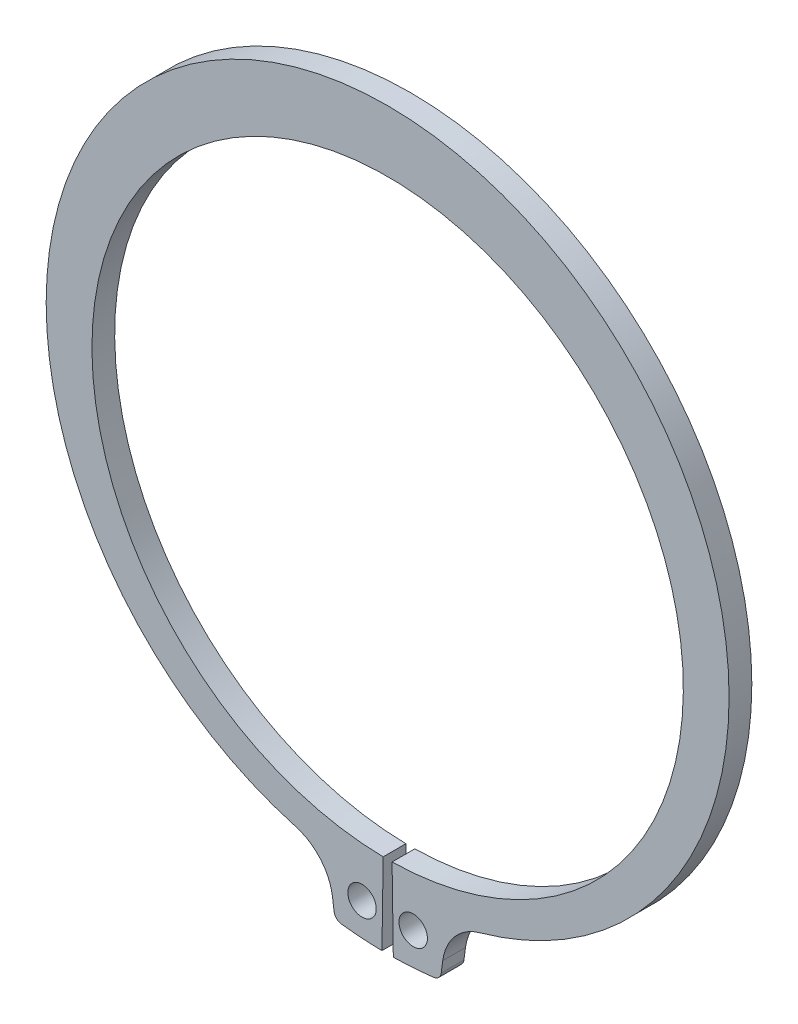
SolidWorks part; units mm, degrees
material "Stahl"
ref_plane "Plane1" through (0, 0, 0) normal (0, 0, 1) x (1, 0, 0)
ref_plane "Plane2" through (0, 0, 0) normal (0, 1, 0) x (1, 0, 0)
ref_plane "Plane3" through (0, 0, 0) normal (1, 0, 0) x (0, 0, -1)
sketch "Clipboard" plane through (0, 0, 0) normal (0, 0, 1) x (1, 0, 0)
  line L0 (0, 0) -> (5.4, 0)
  line L1 (0, 0) -> (0, 2.7)
  line L2 (0, 0) -> (0, -7.2)
  circle A0 centre (0, 0) radius 1.25
  circle A1 centre (0, 0) radius 27.5
  dimension "HoleDia" = 2.5
  dimension "ShaftDia" = 55
  dimension "LargeSection" = 5.4
  dimension "SmallSection" = 2.7
  dimension "LugSection" = 7.2
sketch "BodySke" plane through (0, 0, 0) normal (0, 0, 1) x (1, 0, 0)
  line L0 (-1.5431, 0) -> (1.5431, 0) construction
  line L1 (0, 0) -> (0, 31.4) construction
  line L2 (0.3916, -25.9971) -> (0.5, -33.1962)
  line L3 (-0.3916, -25.9971) -> (-0.5, -33.1962)
  line L4 (0, 0) -> (9.3071, -31.8687) construction
  line L5 (0, 0) -> (-9.3071, -31.8687) construction
  line L7 (4.846, -31.2814) -> (4.7113, -32.3044)
  line L8 (-4.846, -31.2814) -> (-4.7113, -32.3044)
  circle A0 centre (0, 0) radius 26 construction
  arc A1 (0.3916, -25.9971) -> (-0.3916, -25.9971) centre (0, 0) ccw
  arc A2 (8.0456, -27.5492) -> (-8.0456, -27.5492) centre (0, 1.3764) ccw construction
  arc A3 (0.5, -33.1962) -> (4.0594, -32.9509) centre (0, 0) ccw
  arc A4 (8.0941, -27.5357) -> (4.846, -31.2814) centre (9.3071, -31.8687) ccw
  arc A5 (-4.846, -31.2814) -> (-8.0941, -27.5357) centre (-9.3071, -31.8687) ccw
  arc A6 (-4.0594, -32.9509) -> (-0.5, -33.1962) centre (0, 0) ccw
  arc A7 (8.0941, -27.5357) -> (-8.0941, -27.5357) centre (0, 1.3764) ccw
  arc A8 (-5.0237, -29.9313) -> (5.0237, -29.9313) centre (0, 0) ccw construction
  circle A9 centre (2.25, -30.2665) radius 1.25
  circle A10 centre (-2.25, -30.2665) radius 1.25
  arc A11 (4.7113, -32.3044) -> (4.0594, -32.9509) centre (3.9677, -32.2065) cw
  arc A12 (-4.7113, -32.3044) -> (-4.0594, -32.9509) centre (-3.9677, -32.2065) ccw
  point P28 (4.6362, -32.8747)
  point P31 (-4.6362, -32.8747)
  dimension "GrooveDia" = 52
  dimension "D3" = 0.75
  dimension "LugRad" = 33.2
  dimension "HoleOffsetRad" = 30.35
  dimension "HoleDia" = 2.5
  dimension "D2" = 15
  dimension "LargeRad" = 31.4
  dimension "SmallRad" = 28.7
  dimension "Gap" = 1
  dimension "SmallAngle" = 32.56
  dimension "HoleSpacing" = 4.5
extrude "Body" add sketch "BodySke" against normal blind 2
sketch "NotSke" plane through (0, 0, 0) normal (0, 0, 1) x (1, 0, 0)
  line L0 (2.25, -29.0165) -> (2.25, -31.5165)
  line L1 (2.25, -31.5165) -> (-2.25, -31.5165)
  line L2 (-2.25, -31.5165) -> (-2.25, -29.0165)
  line L3 (-2.25, -29.0165) -> (2.25, -29.0165)
  circle A0 centre (2.25, -30.2665) radius 1.25 construction
  circle A1 centre (-2.25, -30.2665) radius 1.25 construction
extrude "Notch" [suppressed] cut sketch "NotSke" against normal through all
sketch "UnlSke" plane through (0, 0, 0) normal (0, 0, 1) x (1, 0, 0)
  line L0 (-3.8228, -32.9792) -> (-2.9938, -25.8271)
  line L1 (3.8228, -32.9792) -> (2.9938, -25.8271)
  arc A0 (2.9938, -25.8271) -> (-2.9938, -25.8271) centre (0, 0) ccw
  arc A1 (3.8228, -32.9792) -> (-3.8228, -32.9792) centre (0, 0) ccw
  arc A2 (0.5, -33.1962) -> (4.0594, -32.9509) centre (0, 0) ccw construction
  arc A3 (0.3916, -25.9971) -> (-0.3916, -25.9971) centre (0, 0) ccw construction
  circle A4 centre (-2.25, -30.2665) radius 1.25 construction
  circle A5 centre (2.25, -30.2665) radius 1.25 construction
extrude "Unlug" [suppressed] add sketch "UnlSke" against normal through all
equation "' \"ShaftDia@Clipboard\" = 3"
equation "' \"Thickness@Body\" = 0.4"
equation "' \"GrooveDia@BodySke\" = 2.8"
equation "' \"LugSection@Clipboard\" = 1.9"
equation "' \"LargeSection@Clipboard\" = 0.8"
equation "' \"HoleDia@Clipboard\" = 1.0"
equation "' \"ShaftDia@Clipboard\" = 10"
equation "' \"Thickness@Body\" = 1.0"
equation "' \"GrooveDia@BodySke\" = 9.6"
equation "' \"LugSection@Clipboard\" = 3.3"
equation "' \"LargeSection@Clipboard\" = 1.8"
equation "' \"HoleDia@Clipboard\" = 1.5"
equation "\"SmallSection@Clipboard\" = \"LargeSection@Clipboard\" * 0.5"
equation "\"Gap@BodySke\" =  \"Thickness@Body\" / 2"
equation "\"LargeRad@BodySke\" =  \"GrooveDia@BodySke\" / 2 +  \"LargeSection@Clipboard\""
equation "\"SmallRad@BodySke\" =  \"GrooveDia@BodySke\" / 2 +  \"SmallSection@Clipboard\""
equation "\"LugRad@BodySke\" = \"GrooveDia@BodySke\" / 2 + \"LugSection@Clipboard\""
equation "\"HoleOffsetRad@BodySke\" = (  \"ShaftDia@Clipboard\" / 2 + \"LugRad@BodySke\" ) / 2"
equation "\"HoleSpacing@BodySke\" = \"Gap@BodySke\"  * 2 +  \"HoleDia@Clipboard\""
equation "\"HoleDia@BodySke\" =  \"HoleDia@Clipboard\""
equation "\"SmallAngle@BodySke\" = atn(\"HoleSpacing@BodySke\" / 2 / sqr(\"HoleOffsetRad@BodySke\"  * \"HoleOffsetRad@BodySke\" - (\"HoleSpacing@BodySke\" / 2) * (\"HoleSpacing@BodySke\" / 2) ))  * 7 *  (\"LargeRad@BodySke\" / \"SmallRad@BodySke\")* ( 180 / 3.141593)"
